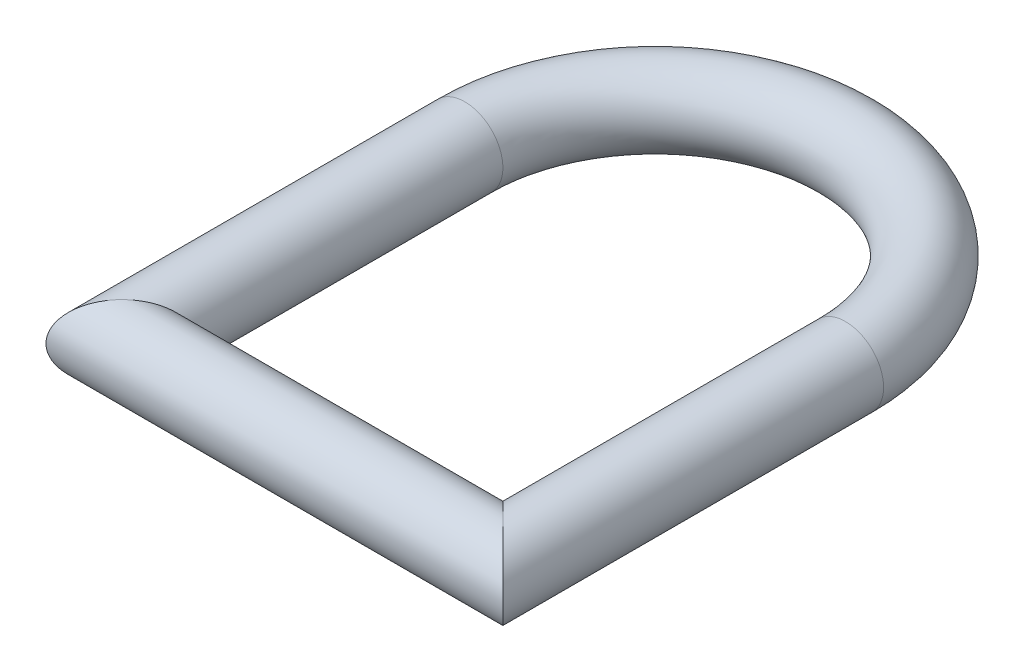
SolidWorks part; units mm, degrees
ref_plane "前视基准面" through (0, 0, 0) normal (0, 0, 1) x (1, 0, 0)
ref_plane "上视基准面" through (0, 0, 0) normal (0, 1, 0) x (1, 0, 0)
ref_plane "右视基准面" through (0, 0, 0) normal (1, 0, 0) x (0, 0, -1)
sketch "草图1" plane through (0, 0, 0) normal (0, 0, 1) x (1, 0, 0)
  line L0 (0, 0) -> (0, 155.4954) construction
  circle A0 centre (250, 0) radius 50
  circle A1 centre (250, 0) radius 47.5
  dimension "D1" = 100
  dimension "D3" = 95
  dimension "D2" = 250
revolve "旋转1" add sketch "草图1" angle 360 about L0
sketch "草图2" plane through (0, 0, 0) normal (0, 1, 0) x (1, 0, 0)
  line L0 (-384.2616, 0) -> (443.1099, 0)
  line L1 (443.1099, 0) -> (321.9175, -325.996)
  line L2 (321.9175, -325.996) -> (-266.5651, -318.4215)
  line L3 (-266.5651, -318.4215) -> (-384.2616, 0)
extrude "切除-拉伸1" cut sketch "草图2" against normal mid plane 300
sketch "草图3" plane through (0, 0, 0) normal (0, 0, 1) x (1, 0, 0)
  circle A0 centre (250, 0) radius 50
  circle A2 centre (250, 0) radius 47.5
extrude "凸台-拉伸1" add sketch "草图3" along normal blind 350
mirror "镜向1" about plane through (0, 0, 0) normal (1, 0, 0) of "凸台-拉伸1"
sketch "草图4" plane through (0, 0, 0) normal (0, 1, 0) x (1, 0, 0)
  line L0 (250, -350) -> (250, -450)
  line L1 (200, -350) -> (300, -350) construction
  line L2 (250, -450) -> (0, -450)
  dimension "D1" = 100
sketch "草图5" plane through (0, 0, 350) normal (0, 0, 1) x (1, 0, 0)
  line L0 (250, 0) -> (0, 0) construction
  circle A0 centre (250, 0) radius 47.5
  circle A1 centre (250, 0) radius 50
sweep "扫描1" add profiles "草图5" path "草图4"
mirror "镜向2" about plane through (0, 0, 0) normal (1, 0, 0) of "扫描1"
sketch "草图6" plane through (0, 0, 0) normal (0, 1, 0) x (1, 0, 0)
  line L0 (300, 0) -> (300, -500)
  line L1 (300, -500) -> (-300, -500)
  line L2 (-300, -500) -> (-300, 0)
  line L3 (-200, 0) -> (-200, -400)
  line L4 (-200, -400) -> (200, -400)
  line L5 (200, -400) -> (200, 0)
  arc A1 (200, 0) -> (-200, 0) centre (0, 0) ccw
  arc A2 (300, 0) -> (-300, 0) centre (0, 0) ccw
